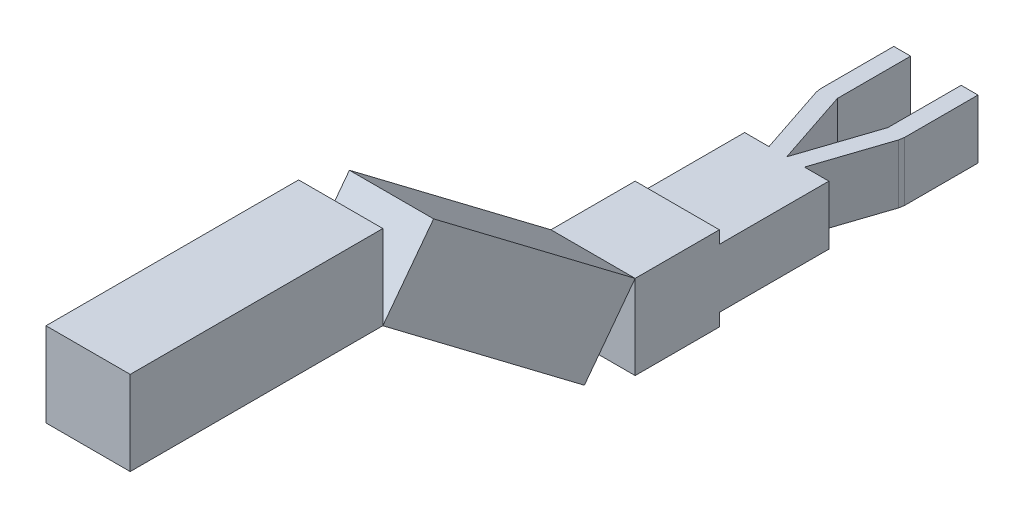
SolidWorks part; units mm, degrees
ref_plane "Front Plane" through (0, 0, 0) normal (0, 0, 1) x (1, 0, 0)
ref_plane "Top Plane" through (0, 0, 0) normal (0, 1, 0) x (1, 0, 0)
ref_plane "Right Plane" through (0, 0, 0) normal (1, 0, 0) x (0, 0, -1)
sketch "Sketch1" plane through (0, 0, 0) normal (0, 1, 0) x (1, 0, 0)
  line L0 (0, -105.7688) -> (-30, -15.63)
  line L1 (-50, 71.37) -> (-30, 71.37)
  line L2 (-50, 71.37) -> (-50, -15.63)
  line L4 (-30, 71.37) -> (-30, -15.63)
  line L5 (30, 71.37) -> (50, 71.37)
  line L6 (30, 71.37) -> (30, -15.63)
  line L8 (50, 71.37) -> (50, -15.63)
  line L9 (21.0786, -105.7688) -> (50, -105.7688)
  line L11 (-21.0786, -105.7688) -> (-48.9766, -21.9458)
  line L12 (0, -105.7688) -> (30, -15.63)
  line L13 (-48.9766, -21.9458) -> (-50, -15.63)
  line L15 (21.0786, -105.7688) -> (48.9766, -21.9458)
  line L16 (-30, 0) -> (0, 0) construction
  line L17 (0, 0) -> (30, 0) construction
  line L18 (50, -15.63) -> (48.9766, -21.9458)
  line L19 (-50, -105.7688) -> (-21.0786, -105.7688)
  line L20 (-50, -105.7688) -> (-50, -235.7688)
  line L21 (-50, -235.7688) -> (50, -235.7688)
  line L22 (50, -105.7688) -> (50, -235.7688)
  dimension "D1" = 20
  dimension "D2" = 20
  dimension "D3" = 60
  dimension "D4" = 87
  dimension "D5" = 95
  dimension "D6" = 100
  dimension "D7" = 130
  dimension "D8" = 20
  dimension "D9" = 20
extrude "Boss-Extrude1" add sketch "Sketch1" along normal blind 70
sketch "Sketch2" plane through (0, 0, 235.7688) normal (0, 0, 1) x (1, 0, 0)
  line L0 (0, 70) -> (0, 0) construction
  line L1 (50, 85) -> (-50, 85)
  line L2 (50, 85) -> (50, -15)
  line L3 (50, -15) -> (-50, -15)
  line L4 (-50, 85) -> (-50, -15)
  line L5 (-50, 70) -> (50, 70) construction
  line L6 (-50, 0) -> (50, 0) construction
  line L7 (0, 0) -> (50, 35) construction
  line L8 (50, 70) -> (50, 0) construction
  line L9 (50, 35) -> (-50, 35) construction
  line L10 (-50, 70) -> (-50, 0) construction
  line L11 (50, 70) -> (0, 35) construction
  line L12 (0, 35) -> (-50, 0) construction
  line L13 (0, 85) -> (0, -15) construction
  point P23 (0, 35)
  dimension "D1" = 100
  dimension "D2" = 100
extrude "Boss-Extrude2" add sketch "Sketch2" along normal blind 100
sketch "Sketch3" plane through (-50, 0, 0) normal (-1, 0, 0) x (0, 0, 1)
  line L0 (335.7688, 85) -> (396.0621, 5.2208)
  line L1 (335.7688, 85) -> (575.1064, 265.8799)
  line L2 (396.0621, 5.2208) -> (635.3996, 186.1007)
  line L3 (575.1064, 265.8799) -> (635.3996, 186.1007)
  dimension "D1" = 100
  dimension "D2" = 300
extrude "Boss-Extrude3" add sketch "Sketch3" against normal blind 100 separate body
sketch "Sketch4" plane through (-50, 0, 0) normal (-1, 0, 0) x (0, 0, 1)
  line L0 (635.3996, 186.1007) -> (935.3996, 186.1007)
  line L1 (635.3996, 186.1007) -> (635.3996, 286.1007)
  line L2 (935.3996, 186.1007) -> (935.3996, 286.1007)
  line L3 (635.3996, 286.1007) -> (935.3996, 286.1007)
  dimension "D1" = 100
  dimension "D2" = 300
extrude "Boss-Extrude4" add sketch "Sketch4" against normal blind 100 separate body
